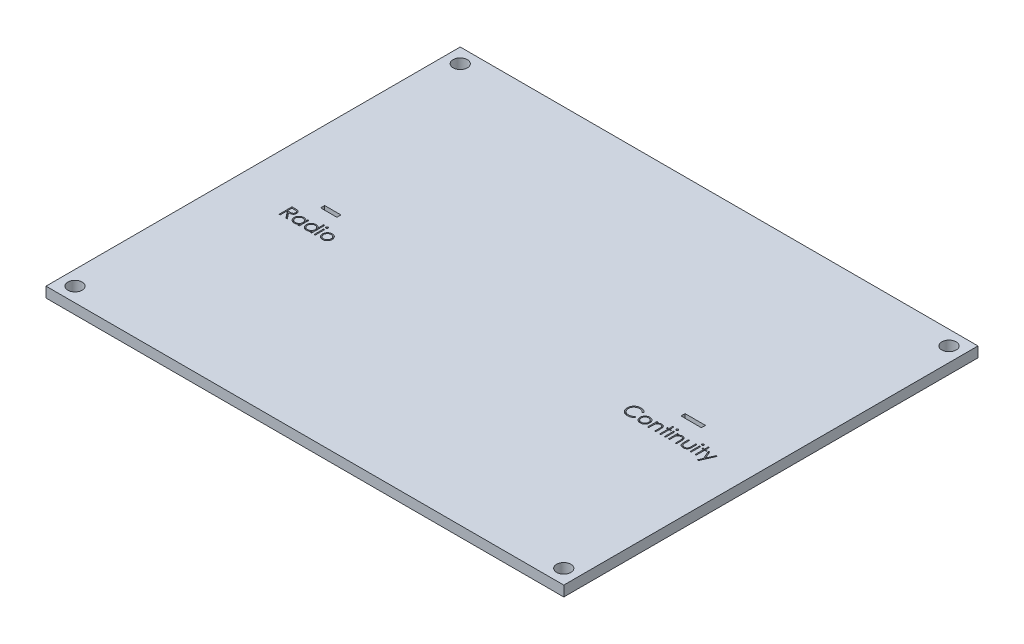
SolidWorks part; units mm, degrees
ref_plane "Front Plane" through (0, 0, 0) normal (0, 0, 1) x (1, 0, 0)
ref_plane "Top Plane" through (0, 0, 0) normal (0, 1, 0) x (1, 0, 0)
ref_plane "Right Plane" through (0, 0, 0) normal (1, 0, 0) x (0, 0, -1)
sketch "Çizim1" plane through (0, 0, 0) normal (0, 1, 0) x (1, 0, 0)
  line L1 (-63.5, 50.8) -> (63.5, 50.8)
  line L2 (-63.5, 50.8) -> (-63.5, -50.8)
  line L3 (-63.5, -50.8) -> (63.5, -50.8)
  line L4 (63.5, 50.8) -> (63.5, -50.8)
  line L5 (-63.5, 50.8) -> (63.5, -50.8) construction
  line L6 (-63.5, -50.8) -> (63.5, 50.8) construction
  point P0 (0, 0)
  dimension "D1" = 127
  dimension "D2" = 101.6
extrude "Yükseklik-Ekstrüzyon1" add sketch "Çizim1" along normal blind 2.54
sketch "Çizim3" plane through (0, 0, 0) normal (0, -1, 0) x (1, 0, 0)
  line L1 (-56.515, 43.815) -> (56.515, 43.815)
  line L2 (-56.515, 43.815) -> (-56.515, -43.815)
  line L3 (-56.515, -43.815) -> (56.515, -43.815)
  line L4 (56.515, 43.815) -> (56.515, -43.815)
  line L5 (-56.515, 43.815) -> (56.515, -43.815) construction
  line L6 (-56.515, -43.815) -> (56.515, 43.815) construction
  point P0 (0, 0)
  dimension "D1" = 113.03
  dimension "D2" = 87.63
extrude "Yükseklik-Ekstrüzyon2" add sketch "Çizim3" along normal blind 1.27 contours L1 L4 L3 L2
sketch "Çizim4" plane through (0, 2.54, 0) normal (0, 1, 0) x (1, 0, 0)
  line L0 (63.5, 50.8) -> (-63.5, 50.8) construction
  line L1 (-63.5, 50.8) -> (-63.5, -50.8) construction
  circle A0 centre (-59.944, 47.244) radius 1.7526
  dimension "D1" = 3.556
  dimension "D2" = 3.556
sketch "Çizim5" plane through (0, 2.54, 0) normal (0, 1, 0) x (1, 0, 0)
  line L0 (63.5, 50.8) -> (-63.5, 50.8) construction
  line L1 (63.5, -50.8) -> (63.5, 50.8) construction
  circle A0 centre (59.944, 47.244) radius 1.7526
  dimension "D1" = 3.556
  dimension "D2" = 3.556
extrude "Kes-Ekstrüzyon1" cut sketch "Çizim4" against normal blind 2.54 contours A0
extrude "Kes-Ekstrüzyon2" cut sketch "Çizim5" against normal blind 2.54 contours A0
sketch "Çizim7" plane through (0, 2.54, 0) normal (0, 1, 0) x (1, 0, 0)
  line L0 (-63.5, 50.8) -> (-63.5, -50.8) construction
  line L1 (-63.5, -50.8) -> (63.5, -50.8) construction
  circle A0 centre (-59.944, -47.244) radius 1.7526
  dimension "D1" = 3.556
  dimension "D2" = 3.556
extrude "Kes-Ekstrüzyon3" cut sketch "Çizim7" against normal blind 2.54
sketch "Çizim9" plane through (0, 2.54, 0) normal (0, 1, 0) x (1, 0, 0)
  line L0 (63.5, -50.8) -> (63.5, 50.8) construction
  line L1 (-63.5, -50.8) -> (63.5, -50.8) construction
  circle A0 centre (59.944, -47.244) radius 1.7526
  dimension "D1" = 3.556
  dimension "D2" = 3.556
extrude "Kes-Ekstrüzyon4" cut sketch "Çizim9" against normal blind 2.54
sketch "Çizim10" plane through (0, 2.54, 0) normal (0, 1, 0) x (1, 0, 0)
  line L0 (-63.5, 50.8) -> (-63.5, -50.8) construction
  line L2 (-46.45, 0.5) -> (-42.45, 0.5)
  line L3 (-46.45, 0.5) -> (-46.45, -0.5)
  line L4 (-46.45, -0.5) -> (-42.45, -0.5)
  line L5 (-42.45, 0.5) -> (-42.45, -0.5)
  line L6 (-46.45, 0.5) -> (-42.45, -0.5) construction
  line L7 (-46.45, -0.5) -> (-42.45, 0.5) construction
  point P0 (-44.45, 0)
  dimension "D1" = 19.05
  dimension "D2" = 1
  dimension "D3" = 4
extrude "Kes-Ekstrüzyon5" cut sketch "Çizim10" against normal blind 3.81
sketch "Çizim11" plane through (0, 2.54, 0) normal (0, 1, 0) x (1, 0, 0)
  line L0 (63.5, -50.8) -> (63.5, 50.8) construction
  line L6 (41.95, 0.5) -> (46.95, 0.5)
  line L7 (41.95, 0.5) -> (41.95, -0.5)
  line L8 (41.95, -0.5) -> (46.95, -0.5)
  line L9 (46.95, 0.5) -> (46.95, -0.5)
  line L10 (41.95, 0.5) -> (46.95, -0.5) construction
  line L11 (41.95, -0.5) -> (46.95, 0.5) construction
  point P0 (44.45, 0)
  dimension "D3" = 5
  dimension "D1" = 19.05
  dimension "D2" = 1
sketch "Çizim12" plane through (0, 2.54, 0) normal (0, 1, 0) x (1, 0, 0)
  text T0 "Radio\r\n"
sketch "Çizim13" plane through (0, 2.54, 0) normal (0, 1, 0) x (1, 0, 0)
  text T0 "Continuity"
  dimension "D1" = 0
  dimension "D2" = 83.9782
extrude "Kes-Ekstrüzyon9" cut sketch "Çizim12" against normal blind 0.762
extrude "Kes-Ekstrüzyon10" cut sketch "Çizim13" against normal blind 0.762
extrude "Kes-Ekstrüzyon11" cut sketch "Çizim11" against normal blind 3.81
